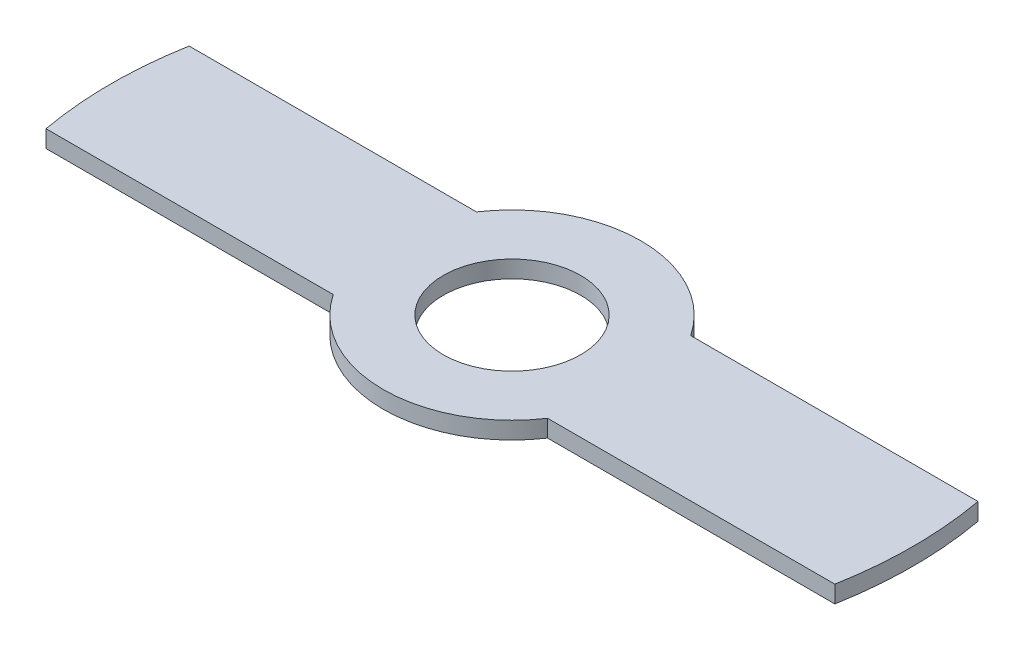
SolidWorks part; units mm, degrees
ref_plane "Alzado" through (0, 0, 0) normal (0, 0, 1) x (1, 0, 0)
ref_plane "Planta" through (0, 0, 0) normal (0, 1, 0) x (1, 0, 0)
ref_plane "Vista lateral" through (0, 0, 0) normal (1, 0, 0) x (0, 0, -1)
sketch "Croquis1" plane through (0, 0, 0) normal (0, 1, 0) x (1, 0, 0)
  line L19 (-18.7083, 12.5) -> (-68.8749, 12.5)
  line L28 (18.7083, 12.5) -> (68.8749, 12.5)
  line L30 (18.7083, -12.5) -> (68.8749, -12.5)
  line L31 (-18.7083, -12.5) -> (-68.8749, -12.5)
  circle A0 centre (0, 0) radius 12
  arc A2 (-68.8749, 12.5) -> (-68.8749, -12.5) centre (0, 0) ccw
  arc A4 (-18.7083, -12.5) -> (18.7083, -12.5) centre (0, 0) ccw
  arc A5 (18.7083, 12.5) -> (-18.7083, 12.5) centre (0, 0) ccw
  arc A6 (68.8749, -12.5) -> (68.8749, 12.5) centre (0, 0) ccw
  point P26 (0, 0)
  point P47 (0, 0)
  point P88 (0, 0)
  point P92 (0, 0)
  dimension "D1" = 24
extrude "Saliente-Extruir1" add sketch "Croquis1" along normal blind 3
